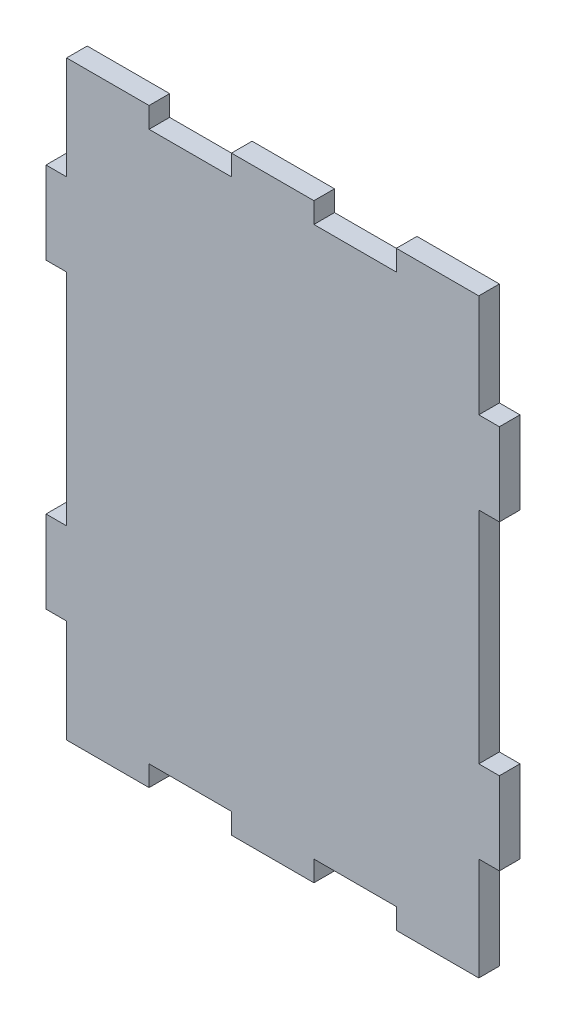
SolidWorks part; units mm, degrees
material "Pinho"
ref_plane "Plano frontal" through (0, 0, 0) normal (0, 0, 1) x (1, 0, 0)
ref_plane "Plano superior" through (0, 0, 0) normal (0, 1, 0) x (1, 0, 0)
ref_plane "Plano direito" through (0, 0, 0) normal (1, 0, 0) x (0, 0, -1)
sketch "Esboço1" plane through (0, 0, 0) normal (0, 0, 1) x (1, 0, 0)
  line L0 (-31.2169, 9.3483) -> (-31.2169, -22.6517)
  line L1 (-19.2169, 33.3483) -> (-7.2169, 33.3483)
  line L2 (-31.2169, 33.3483) -> (-31.2169, 21.3483)
  line L3 (-19.2169, -46.6517) -> (-7.2169, -46.6517)
  line L4 (28.7831, 33.3483) -> (28.7831, 21.3483)
  line L5 (-31.2169, -34.6517) -> (-31.2169, -46.6517)
  line L6 (-31.2169, 9.3483) -> (-34.2169, 9.3483)
  line L7 (4.7831, 33.3483) -> (16.7831, 33.3483)
  line L9 (-31.2169, 21.3483) -> (-34.2169, 21.3483)
  line L10 (-34.2169, 9.3483) -> (-34.2169, 21.3483)
  line L12 (-31.2169, 33.3483) -> (-31.2169, 36.3483)
  line L13 (-34.2169, -34.6517) -> (-31.2169, -34.6517)
  line L14 (-34.2169, -34.6517) -> (-34.2169, -22.6517)
  line L15 (-34.2169, -22.6517) -> (-31.2169, -22.6517)
  line L17 (-31.2169, 36.3483) -> (-19.2169, 36.3483)
  line L18 (-19.2169, 33.3483) -> (-19.2169, 36.3483)
  line L20 (28.7831, 33.3483) -> (28.7831, 36.3483)
  line L21 (28.7831, 36.3483) -> (16.7831, 36.3483)
  line L22 (16.7831, 33.3483) -> (16.7831, 36.3483)
  line L24 (-7.2169, 33.3483) -> (-7.2169, 36.3483)
  line L25 (-7.2169, 36.3483) -> (4.7831, 36.3483)
  line L26 (4.7831, 33.3483) -> (4.7831, 36.3483)
  line L27 (28.7831, -34.6517) -> (28.7831, -46.6517)
  line L28 (28.7831, 9.3483) -> (31.7831, 9.3483)
  line L30 (28.7831, 21.3483) -> (31.7831, 21.3483)
  line L31 (31.7831, 9.3483) -> (31.7831, 21.3483)
  line L32 (4.7831, -46.6517) -> (16.7831, -46.6517)
  line L34 (28.7831, -34.6517) -> (31.7831, -34.6517)
  line L36 (28.7831, -22.6517) -> (31.7831, -22.6517)
  line L37 (31.7831, -34.6517) -> (31.7831, -22.6517)
  line L38 (28.7831, 9.3483) -> (28.7831, -22.6517)
  line L39 (-31.2169, -46.6517) -> (-31.2169, -49.6517)
  line L40 (-31.2169, -49.6517) -> (-19.2169, -49.6517)
  line L41 (-19.2169, -46.6517) -> (-19.2169, -49.6517)
  line L43 (28.7831, -46.6517) -> (28.7831, -49.6517)
  line L44 (28.7831, -49.6517) -> (16.7831, -49.6517)
  line L45 (16.7831, -46.6517) -> (16.7831, -49.6517)
  line L47 (-7.2169, -46.6517) -> (-7.2169, -49.6517)
  line L48 (-7.2169, -49.6517) -> (4.7831, -49.6517)
  line L49 (4.7831, -46.6517) -> (4.7831, -49.6517)
  point P0 (0, 0)
  dimension "D1" = 80
  dimension "D2" = 60
  dimension "D3" = 12
  dimension "D4" = 12
  dimension "D5" = 12
  dimension "D6" = 12
  dimension "D7" = 12
  dimension "D8" = 12
  dimension "D9" = 12
  dimension "D10" = 12
  dimension "D11" = 12
  dimension "D12" = 12
  dimension "D13" = 12
  dimension "D14" = 12
  dimension "D15" = 12
  dimension "D16" = 12
  dimension "D17" = 3
  dimension "D18" = 3
  dimension "D19" = 3
  dimension "D20" = 3
  dimension "D21" = 3
  dimension "D22" = 3
  dimension "D23" = 3
  dimension "D24" = 3
  dimension "D25" = 3
  dimension "D26" = 3
  dimension "D27" = 3
  dimension "D28" = 3
  dimension "D29" = 3
  dimension "D30" = 12
  dimension "D31" = 3
extrude "Ressalto-extrusão1" add sketch "Esboço1" along normal blind 3
